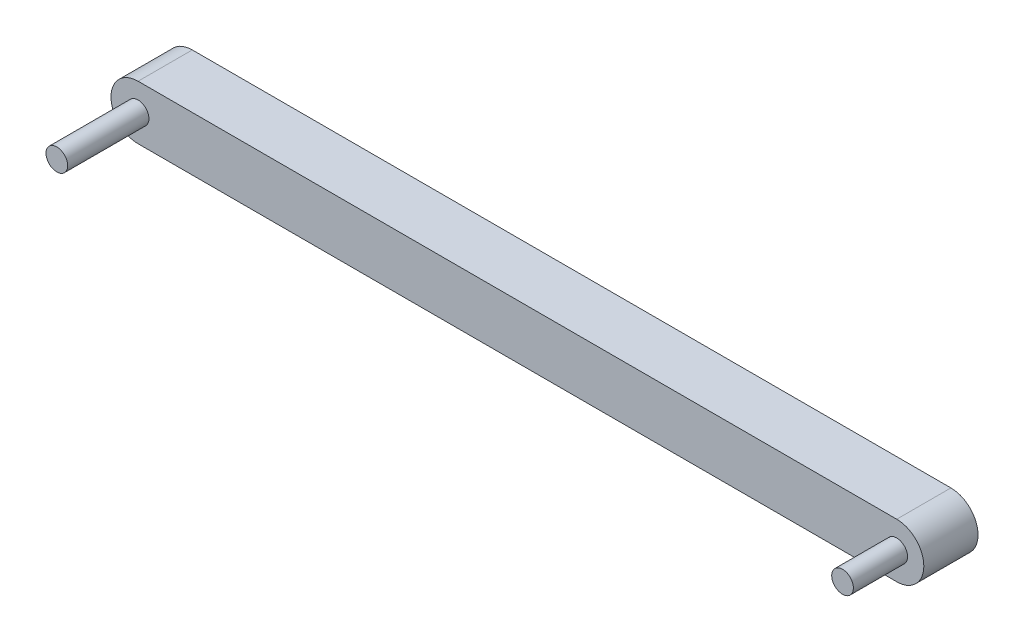
SolidWorks part; units mm, degrees
ref_plane "Front Plane" through (0, 0, 0) normal (0, 0, 1) x (1, 0, 0)
ref_plane "Top Plane" through (0, 0, 0) normal (0, 1, 0) x (1, 0, 0)
ref_plane "Right Plane" through (0, 0, 0) normal (1, 0, 0) x (0, 0, -1)
sketch "Sketch1" plane through (0, 0, 0) normal (0, 0, 1) x (1, 0, 0)
  line L0 (0, 0) -> (1400, 0)
  line L1 (0, 0) -> (0, 50)
  line L2 (1400, 0) -> (1400, 50)
  line L3 (0, 100) -> (1400, 100)
  arc A0 (1400, 0) -> (1400, 100) centre (1400, 50) ccw
  arc A1 (0, 0) -> (0, 100) centre (0, 50) cw
extrude "Boss-Extrude1" add sketch "Sketch1" along normal blind 100
sketch "Sketch2" plane through (0, 0, 100) normal (0, 0, 1) x (1, 0, 0)
  line L0 (0, 0) -> (0, 50)
  line L1 (1400, 0) -> (1400, 50)
  circle A0 centre (0, 50) radius 20
  circle A1 centre (1400, 50) radius 20
extrude "Boss-Extrude3" add sketch "Sketch2" along normal blind 150 contours A0
sketch "Sketch4" plane through (0, 0, 100) normal (0, 0, 1) x (1, 0, 0)
  line L0 (1400, 0) -> (1400, 50)
  circle A0 centre (1400, 50) radius 20
extrude "Boss-Extrude4" add sketch "Sketch4" along normal blind 100
